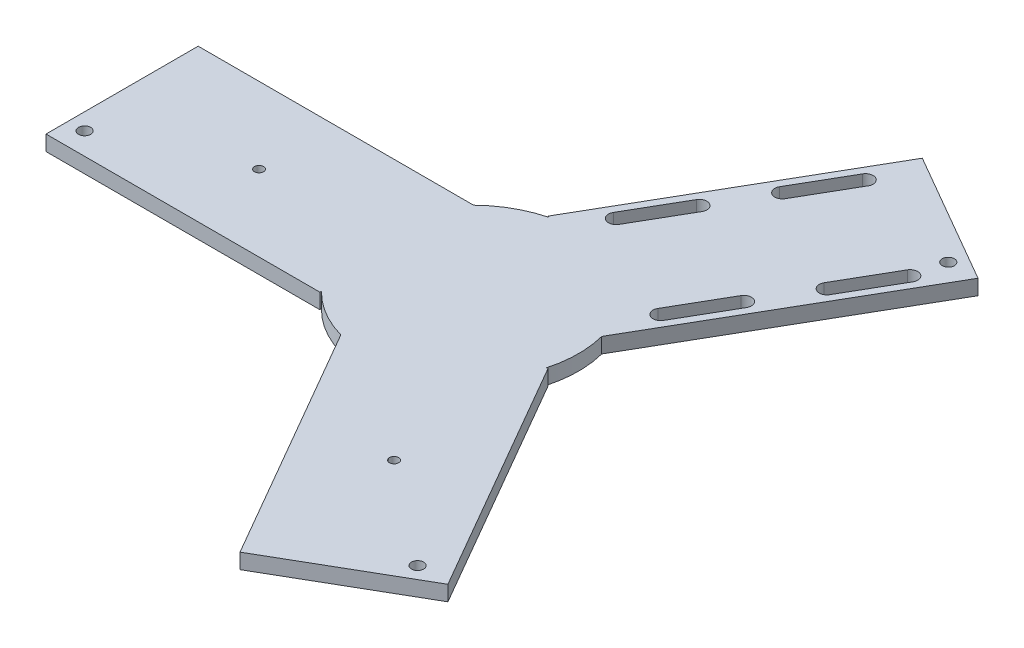
SolidWorks part; units mm, degrees
ref_plane "Plan de face" through (0, 0, 0) normal (0, 0, 1) x (1, 0, 0)
ref_plane "Plan de dessus" through (0, 0, 0) normal (0, 1, 0) x (1, 0, 0)
ref_plane "Plan de droite" through (0, 0, 0) normal (1, 0, 0) x (0, 0, -1)
sketch "Esquisse3" plane through (0, 0, 0) normal (0, 1, 0) x (1, 0, 0)
  line L0 (-150.1573, 0) -> (189.6273, 0) construction
  line L1 (-83.8395, -145.9242) -> (87.7229, 151.2306) construction
  line L2 (-78.0725, 135.2255) -> (117.7517, -203.9519) construction
  line L3 (-125, 131.2995) -> (-125, -153.5705) construction
  line L4 (-25, -25) -> (-115, -25)
  line L6 (-25, 25) -> (-24.4949, 25)
  line L7 (-115, -25) -> (-115, 25)
  line L8 (-25, -25) -> (-115, 25) construction
  line L9 (-25, 25) -> (-115, -25) construction
  line L10 (-24.4949, 25) -> (-115, 25)
  line L11 (33.8981, 8.7132) -> (79.1506, 87.0929)
  line L12 (35.8494, 112.0929) -> (79.1506, 87.0929)
  line L13 (-9.1506, 34.1506) -> (35.8494, 112.0929)
  line L14 (-9.4032, -33.7132) -> (35.8494, -112.0929)
  line L15 (79.1506, -87.0929) -> (35.8494, -112.0929)
  line L16 (34.1506, -9.1506) -> (79.1506, -87.0929)
  line L17 (-24.4949, 25) -> (-25, -25)
  line L18 (-9.1506, 34.1506) -> (33.8981, 8.7132)
  line L19 (-9.4032, -33.7132) -> (34.1506, -9.1506)
  circle A0 centre (0, 0) radius 125
  circle A1 centre (0, 0) radius 35
  circle A2 centre (0, 0) radius 125
  circle A3 centre (0, 0) radius 125
  point P9 (-70, 0)
  point P32 (0, 0)
  dimension "D1" = 250
  dimension "D4" = 70
  dimension "D2" = 120
  dimension "D3" = 120
  dimension "D5" = 10
  dimension "D6" = 50
  dimension "D7" = 90
  dimension "D8" = 3
extrude "Boss.-Extru.3" add sketch "Esquisse3" along normal blind 5 contours A1 L6 L10 L7 L4 L17 | A1 L14 L15 L16 L19 | L19 A1 L18 L17 | A1 L11 L12 L13 L18 | L18 A1
sketch "Esquisse5" plane through (0, 5, 0) normal (0, 1, 0) x (1, 0, 0)
  line L0 (79.1506, -87.0929) -> (35.8494, -112.0929) construction
  line L1 (57.5, -99.5929) -> (18.2832, -31.6674) construction
  line L2 (79.1506, -87.0929) -> (35.8494, -112.0929)
  line L3 (57.5, 99.5929) -> (8.3012, 14.3781) construction
  line L4 (35.8494, 112.0929) -> (79.1506, 87.0929) construction
  line L7 (35.8494, 112.0929) -> (79.1506, 87.0929)
  line L8 (69.4856, 75.3525) -> (59.4856, 58.032)
  line L9 (55.1554, 60.532) -> (65.1554, 77.8525)
  line L10 (-9.1506, 34.1506) -> (35.8494, 112.0929) construction
  line L11 (-9.1506, 34.1506) -> (35.8494, 112.0929)
  line L12 (13.3494, 73.1218) -> (72.6977, 38.857) construction
  line L13 (45.1554, 43.2115) -> (35.1554, 25.891)
  line L14 (39.4856, 23.391) -> (49.4856, 40.7115)
  line L15 (24.8446, 78.032) -> (34.8446, 95.3525)
  line L16 (30.5144, 97.8525) -> (20.5144, 80.532)
  line L17 (0.5144, 45.891) -> (10.5144, 63.2115)
  line L18 (14.8446, 60.7115) -> (4.8446, 43.391)
  line L19 (-115, -25) -> (-115, 25) construction
  line L20 (-115, -25) -> (-115, 25)
  line L21 (-115, 0) -> (-25, 0) construction
  circle A0 centre (35, -60.6218) radius 1.5
  arc A3 (59.4856, 58.032) -> (55.1554, 60.532) centre (57.3205, 59.282) cw
  arc A4 (65.1554, 77.8525) -> (69.4856, 75.3525) centre (67.3205, 76.6025) cw
  arc A5 (49.4856, 40.7115) -> (45.1554, 43.2115) centre (47.3205, 41.9615) ccw
  arc A6 (35.1554, 25.891) -> (39.4856, 23.391) centre (37.3205, 24.641) ccw
  arc A7 (34.8446, 95.3525) -> (30.5144, 97.8525) centre (32.6795, 96.6025) ccw
  arc A8 (20.5144, 80.532) -> (24.8446, 78.032) centre (22.6795, 79.282) ccw
  arc A9 (4.8446, 43.391) -> (0.5144, 45.891) centre (2.6795, 44.641) cw
  arc A10 (10.5144, 63.2115) -> (14.8446, 60.7115) centre (12.6795, 61.9615) cw
  circle A11 centre (-70, 0) radius 1.5
  point P44 (-75.6931, 0)
  dimension "D2" = 3
  dimension "D7" = 3
  dimension "D1" = 45
  dimension "D3" = 20
  dimension "D4" = 5
  dimension "D5" = 15
  dimension "D6" = 20
  dimension "D8" = 45
extrude "Enlèv. mat.-Extru.1" cut sketch "Esquisse5" against normal through all contours L16 A8 L15 A7 | A10 L17 A9 L18 | A4 L9 A3 L8 | L13 A6 L14 A5 | A0 | A11
sketch "Esquisse7" plane through (0, 5, 0) normal (0, 1, 0) x (1, 0, 0)
  circle A0 centre (69.7224, 86.7628) radius 2 construction
  circle A1 centre (69.7224, 86.7628) radius 2
  circle A2 centre (-109.5626, -17.7577) radius 2 construction
  circle A3 centre (-109.5626, -17.7577) radius 2
  circle A4 centre (68.8476, -86.7628) radius 2 construction
  circle A5 centre (68.8476, -86.7628) radius 2
extrude "Enlèv. mat.-Extru.2" cut sketch "Esquisse7" against normal blind 10
